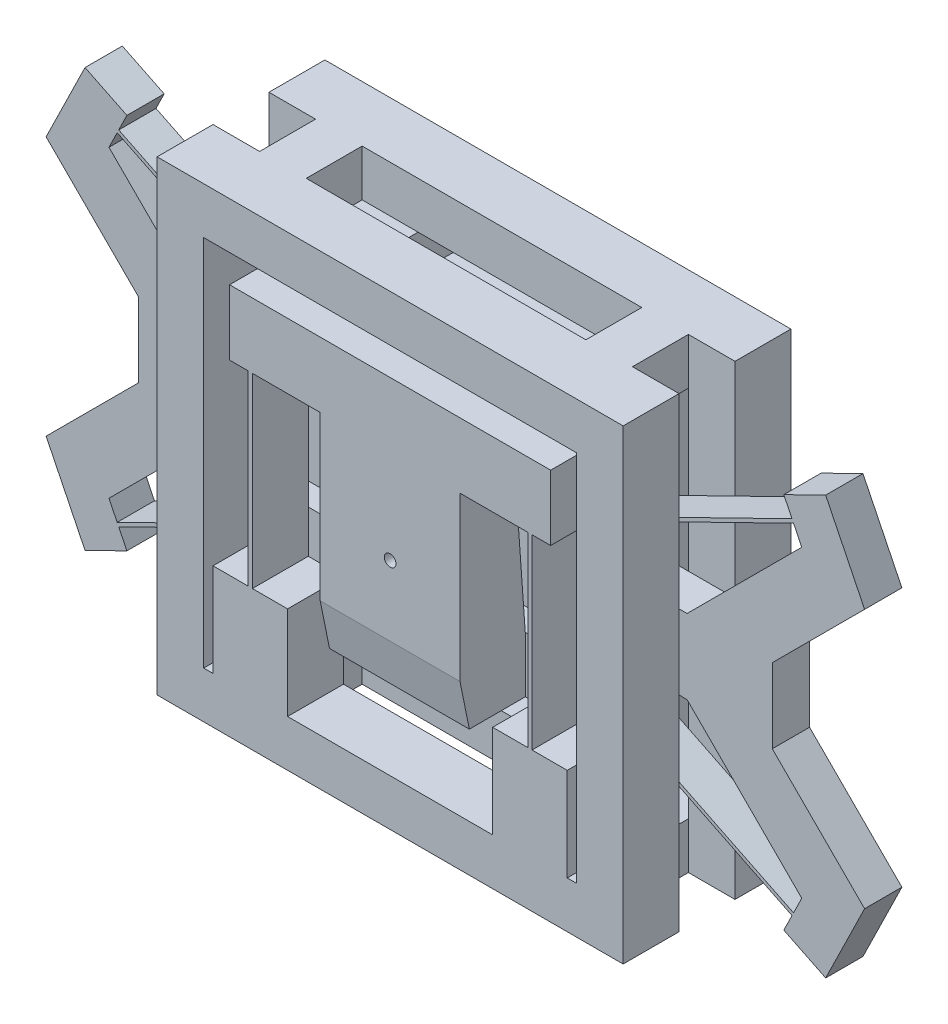
SolidWorks part; units mm, degrees
ref_plane "Front Plane" through (0, 0, 0) normal (0, 0, 1) x (1, 0, 0)
ref_plane "Top Plane" through (0, 0, 0) normal (0, 1, 0) x (1, 0, 0)
ref_plane "Right Plane" through (0, 0, 0) normal (1, 0, 0) x (0, 0, -1)
sketch "Sketch1" plane through (0, 0, 0) normal (0, 0, 1) x (1, 0, 0)
  line L0 (-20, -38) -> (-20, -30.45)
  line L8 (-20, -29.55) -> (-20, -22)
  line L9 (-20, -22) -> (-40, -22)
  line L10 (-40, -22) -> (-40, 22)
  line L11 (-50, 0) -> (-40, 0) construction
  line L12 (-50, 50) -> (-50, -50)
  line L13 (-50, -50) -> (50, -50)
  line L14 (50, -50) -> (50, 50)
  line L15 (40, 0) -> (50, 0) construction
  line L16 (40, 40) -> (40, -40)
  line L17 (40, -40) -> (-40, -40)
  line L18 (-40, -40) -> (-40, -38)
  line L19 (-40, -38) -> (-20, -38)
  line L20 (-20, 30.45) -> (20, 30.45)
  line L21 (20, 30.45) -> (20, 34.45)
  line L22 (20, 34.45) -> (34, 34.45)
  line L23 (34, 34.45) -> (34, -34.45)
  line L24 (-40, 38) -> (-20, 38)
  line L25 (-40, 40) -> (-40, 38)
  line L26 (40, 40) -> (-40, 40)
  line L27 (-50, 50) -> (50, 50)
  line L28 (-20, 22) -> (-40, 22)
  line L29 (-20, 29.55) -> (-20, 22)
  line L37 (-20, 38) -> (-20, 30.45)
  line L38 (34, -34.45) -> (20, -34.45)
  line L39 (20, -34.45) -> (20, -30.45)
  line L40 (-20, -30.45) -> (20, -30.45)
  line L41 (-20, -29.55) -> (20, -29.55)
  line L43 (20, 29.55) -> (-20, 29.55)
  line L44 (20, -29.55) -> (20, -15)
  line L45 (20, -15) -> (-15, -15)
  line L46 (-15, -15) -> (-15, 15)
  line L47 (-15, 15) -> (20, 15)
  line L48 (20, 15) -> (20, 29.55)
  line L49 (-15, 0) -> (0, 0) construction
  point P38 (0, -30.45)
  dimension "D2" = 40
  dimension "D3" = 0.9
  dimension "D4" = 100
  dimension "D5" = 100
  dimension "D6" = 10
  dimension "D7" = 10
  dimension "D8" = 16
  dimension "D9" = 4
  dimension "D10" = 10
  dimension "D11" = 14
  dimension "D12" = 4
  dimension "D13" = 30
  dimension "D14" = 50
  dimension "D15" = 15
  dimension "D16" = 50
  dimension "D17" = 60
  dimension "D18" = 10
extrude "Boss-Extrude1" add sketch "Sketch1" along normal blind 12
sketch "Sketch3" plane through (-15, 0, 0) normal (-1, 0, 0) x (0, 0, 1)
  line L1 (12, -15) -> (12, 15)
  line L2 (12, 15) -> (0, 15) construction
  line L3 (12, -15) -> (12, 15) construction
  line L10 (12, -15) -> (14, 12.85)
  line L11 (14, 12.85) -> (14, 24.85)
  line L14 (12, -15) -> (12, 15)
  line L15 (14, 24.85) -> (0, 15)
  line L16 (0, 15) -> (12, 15)
  line L17 (12, -15) -> (12, 15)
  point P11 (12, 0)
  line M5 (12, -15) -> (12, 15)
  line M6 (12, 15) -> (0, 15)
  dimension "D2" = 2
  dimension "D1" = 12
  dimension "D3" = 12
  dimension "D4" = 24.85
extrude "Boss-Extrude2" add sketch "Sketch3" against normal blind 30 contours L11 L15 L10 M6 M5
sketch "Sketch4" plane through (0, 0, 14) normal (0, 0, 1) x (1, 0, 0)
  line L12 (-6, 24.85) -> (-33.3606, 24.85)
  line L13 (-33.3606, 24.85) -> (-36.135, 19.1868)
  line L14 (-36.135, 19.1868) -> (-72.2357, 36.8723)
  line L15 (-72.2357, 36.8723) -> (-70.476, 40.4644)
  line L16 (-70.476, 40.4644) -> (-79.4563, 44.8638)
  line L17 (-79.4563, 44.8638) -> (-87.8106, 27.8106)
  line L19 (-60, 0) -> (60, 0)
  line L20 (0, 0) -> (0, 8)
  line L21 (49.7188, 8) -> (-49.7188, 8)
  line L22 (-49.7188, 8) -> (-74.3254, 32.6067)
  line L23 (-74.3254, 32.6067) -> (-72.5657, 36.1988)
  line L24 (-72.5657, 36.1988) -> (-36.465, 18.5132)
  line L25 (-36.465, 18.5132) -> (-39.2394, 12.85)
  line L26 (-39.2394, 12.85) -> (39.2394, 12.85)
  line L27 (0, 12.85) -> (0, 24.85)
  line L28 (-87.8106, 27.8106) -> (-68, 8)
  line L29 (6, 24.85) -> (-6, 24.85)
  line L30 (36.135, 19.1868) -> (36.465, 18.5132) construction
  line L31 (-36.135, 19.1868) -> (-36.465, 18.5132) construction
  line L32 (36.465, 18.5132) -> (39.2394, 12.85)
  line L33 (72.5657, 36.1988) -> (36.465, 18.5132)
  line L34 (74.3254, 32.6067) -> (72.5657, 36.1988)
  line L35 (49.7188, 8) -> (74.3254, 32.6067)
  line L37 (79.4563, 44.8638) -> (87.8106, 27.8106)
  line L38 (70.476, 40.4644) -> (79.4563, 44.8638)
  line L39 (72.2357, 36.8723) -> (70.476, 40.4644)
  line L40 (36.135, 19.1868) -> (72.2357, 36.8723)
  line L41 (33.3606, 24.85) -> (36.135, 19.1868)
  line L42 (6, 24.85) -> (33.3606, 24.85)
  line L44 (-68, 8) -> (-68, 0)
  line L45 (-68, 0) -> (-60, 0)
  line L46 (87.8106, 27.8106) -> (68, 8)
  line L47 (68, 8) -> (68, 0)
  line L48 (68, 0) -> (60, 0)
  point P14 (-36.3, 18.85)
  dimension "D1" = 40.2
  dimension "D2" = 0.75
  dimension "D4" = 8
  dimension "D6" = 4
  dimension "D7" = 10
  dimension "D9" = 12
  dimension "D10" = 26.1
  dimension "D11" = 45
  dimension "D12" = 4
  dimension "D5" = 36.3
  dimension "D8" = 18.85
  dimension "D3" = 8
  dimension "D13" = 8
  dimension "D14" = 120
  dimension "D15" = 8
extrude "Boss-Extrude3" add sketch "Sketch4" along normal blind 8
mirror "Mirror6" about plane through (0, 0, 22) normal (0, 1, 0) of "Boss-Extrude3"
sketch "Sketch6" plane through (0, 0, 22) normal (0, 0, 1) x (1, 0, 0)
  line L0 (15, -12.85) -> (15, -24.85) construction
  line L1 (-39.2394, -12.85) -> (39.2394, -12.85) construction
  line L2 (33.3606, -24.85) -> (-33.3606, -24.85) construction
  line L3 (15, -24.85) -> (0, -24.85) construction
  dimension "D1" = 15
ref_plane "Plane1" through (15, 0, 0) normal (-1, 0, 0) x (0, -1, 0)
sketch "Sketch7" plane through (15, 0, 0) normal (-1, 0, 0) x (0, -1, 0)
  line L0 (24.85, 22) -> (12.85, 22)
  line L1 (12.85, 22) -> (24.85, 22) construction
  line L2 (12.85, 22) -> (-15, 24)
  line L7 (15, 36) -> (24.85, 34)
  line L8 (24.85, 34) -> (24.85, 22)
  line L9 (-15, 24) -> (15, 24)
  line L10 (15, 24) -> (15, 36)
  dimension "D2" = 2
  dimension "D3" = 39.85
  dimension "D4" = 12
  dimension "D5" = 0
  dimension "D6" = 12
  dimension "D1" = 12
  dimension "D7" = 30
extrude "Boss-Extrude4" add sketch "Sketch7" along normal blind 30
sketch "Sketch8" plane through (0, 0, 24) normal (0, 0, 1) x (1, 0, 0)
  line L0 (38, -20) -> (30.45, -20)
  line L1 (29.55, -20) -> (22, -20)
  line L2 (22, -20) -> (22, -40)
  line L3 (22, -40) -> (-22, -40)
  line L4 (0, -50) -> (0, -40) construction
  line L5 (-50, -50) -> (50, -50)
  line L6 (50, -50) -> (50, 50)
  line L7 (50, 50) -> (-50, 50)
  line L8 (0, 40) -> (0, 50) construction
  line L9 (-40, 40) -> (40, 40)
  line L10 (40, 40) -> (40, -40)
  line L11 (40, -40) -> (38, -40)
  line L12 (38, -40) -> (38, -20)
  line L13 (-30.45, -20) -> (-30.45, 20)
  line L14 (-30.45, 20) -> (-34.45, 20)
  line L15 (-34.45, 20) -> (-34.45, 34)
  line L16 (-34.45, 34) -> (34.45, 34)
  line L17 (-38, -40) -> (-38, -20)
  line L18 (-40, -40) -> (-38, -40)
  line L19 (-40, 40) -> (-40, -40)
  line L20 (-50, -50) -> (-50, 50)
  line L21 (-22, -20) -> (-22, -40)
  line L22 (-29.55, -20) -> (-22, -20)
  line L23 (-38, -20) -> (-30.45, -20)
  line L24 (34.45, 34) -> (34.45, 20)
  line L25 (34.45, 20) -> (30.45, 20)
  line L26 (30.45, -20) -> (30.45, 20)
  line L27 (29.55, -20) -> (29.55, 20)
  line L28 (-29.55, 20) -> (-29.55, -20)
  line L29 (29.55, 20) -> (-15, 20)
  line L30 (-15, 20) -> (-15, -15)
  line L31 (-15, -15) -> (15, -15)
  line L32 (15, -15) -> (15, 20)
  line L33 (15, 20) -> (-29.55, 20)
  line L34 (0, -15) -> (0, 0) construction
  point P37 (30.45, 0)
  dimension "D1" = 100
  dimension "D2" = 10
  dimension "D3" = 10
  dimension "D4" = 16
  dimension "D5" = 10
  dimension "D6" = 40
  dimension "D7" = 0.9
  dimension "D8" = 4
  dimension "D9" = 14
  dimension "D10" = 4
  dimension "D11" = 30
  dimension "D12" = 15
  dimension "D13" = 50
  dimension "D14" = 60
  dimension "D15" = 100
  dimension "D16" = 10
  dimension "D17" = 0.9
  dimension "D18" = 20
extrude "Boss-Extrude5" add sketch "Sketch8" along normal blind 12
sketch "Sketch9" plane through (0, 0, 12) normal (0, 0, 1) x (1, 0, 0)
  line L1 (30, -40) -> (40, -40)
  line L2 (30, -40) -> (30, -50)
  line L3 (30, -50) -> (40, -50)
  line L4 (40, -40) -> (40, -50)
  line L7 (-40, -40) -> (-30, -40)
  line L8 (-40, -40) -> (-40, -50)
  line L9 (-40, -50) -> (-30, -50)
  line L10 (-30, -40) -> (-30, -50)
  line L12 (-40, 50) -> (-30, 50)
  line L13 (-40, 50) -> (-40, 40)
  line L20 (30, 40) -> (40, 40)
  line L21 (40, 50) -> (40, 40)
  line L23 (-30, 50) -> (-30, 40)
  line L24 (-40, 40) -> (40, 40) construction
  line L25 (-30, 40) -> (-40, 40)
  line L26 (-50, -50) -> (-50, 50) construction
  line L27 (40, 50) -> (30, 50)
  line L28 (50, 50) -> (-50, 50) construction
  line L29 (30, 50) -> (30, 40)
  line L30 (50, -50) -> (50, 50) construction
  line L31 (-50, -50) -> (50, -50) construction
  line L33 (-40, -40) -> (-38, -40) construction
  dimension "D1" = 10
  dimension "D2" = 10
  dimension "D3" = 10
extrude "Boss-Extrude6" add sketch "Sketch9" along normal blind 12
sketch "Sketch17" plane through (0, 0, 36) normal (0, 0, 1) x (1, 0, 0)
  circle A0 centre (0, 0) radius 1.25
  dimension "D1" = 2.5
extrude "Cut-Extrude1" [suppressed] cut sketch "Sketch17" against normal blind 9 contours A0
sketch "Sketch18" plane through (0, 0, 0) normal (0, 0, -1) x (-1, 0, 0)
  line L0 (40, -40) -> (-40, -40) construction
  line L1 (40, -38) -> (40, -40) construction
  line L2 (-50, -50) -> (-50, 50) construction
  line L3 (-40, 40) -> (40, 40) construction
  line L4 (40, 40) -> (40, 38) construction
  circle A0 centre (45, -35) radius 1.25
  circle A1 centre (-45, -35) radius 1.25
  circle A2 centre (-45, 35) radius 1.25
  circle A3 centre (45, 35) radius 1.25
  circle A4 centre (0, 0) radius 1.25
  dimension "D1" = 2.5
  dimension "D4" = 5
  dimension "D2" = 5
  dimension "D3" = 5
  dimension "D5" = 5
  dimension "D6" = 5
  dimension "D7" = 5
  dimension "D8" = 5
  dimension "D9" = 5
extrude "Cut-Extrude2" [suppressed] cut sketch "Sketch18" against normal blind 9.5
sketch "Sketch19" plane through (0, 0, 36) normal (0, 0, 1) x (1, 0, 0)
  circle A0 centre (0, 0) radius 1.25
  dimension "D1" = 2.5
extrude "Cut-Extrude3" cut sketch "Sketch19" against normal blind 6
sketch "Sketch20" plane through (0, 0, 0) normal (0, 0, -1) x (-1, 0, 0)
  circle A0 centre (0, 0) radius 1.25
  dimension "D1" = 2.5
extrude "Cut-Extrude4" cut sketch "Sketch20" against normal blind 6
equation "\"Alpha\"= 26 + 1 / 10deg"
equation "\"L\"= 40 + 2 / 10mm"
equation "\"L1\"= 72 + 6 / 10mm"
equation "\"L2\"= 37 + 7 / 10mm"
equation "\"D1@Sketch4\"=\"L\""
equation "\"D10@Sketch4\"=\"Alpha\""
equation "\"D3@Sketch7\"= \"L2\" / 2 + 21"
equation "\"D5@Sketch4\"=\"L1\"/2"
equation "\"D8@Sketch4\"=\"L2\"/2"
equation "\"D4@Sketch3\"=\"L2\"/2 + 6"
